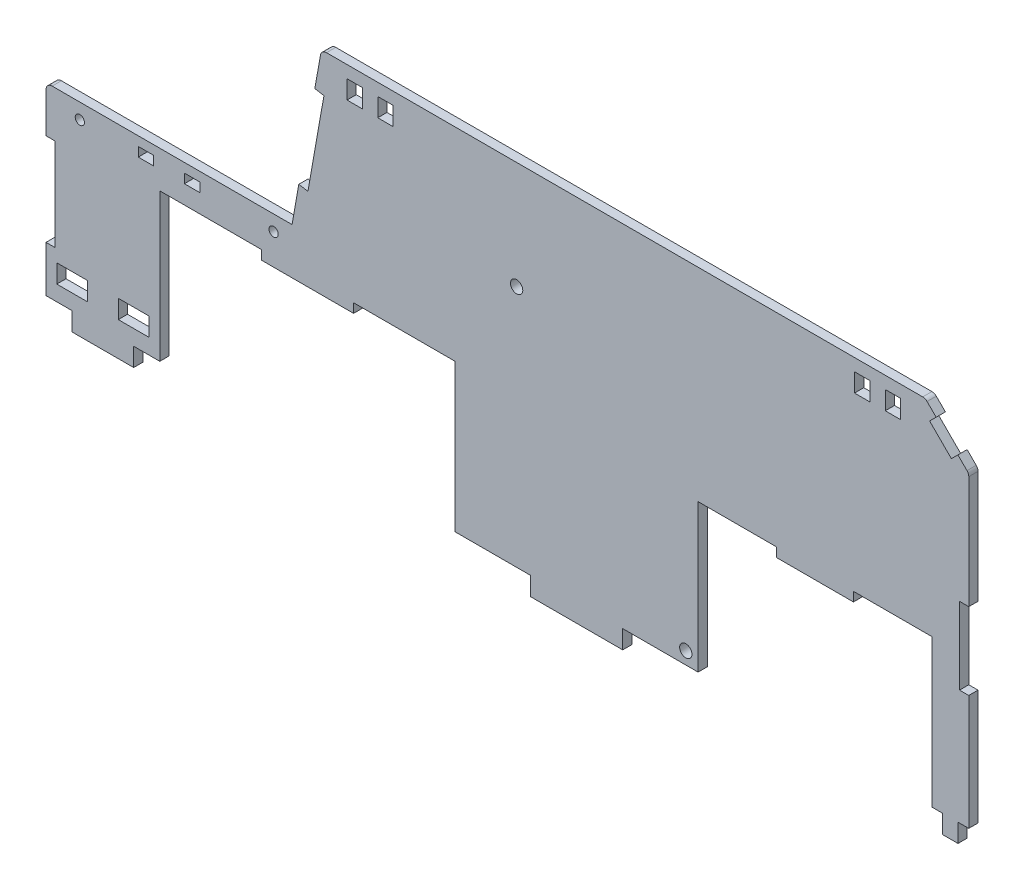
SolidWorks part; units mm, degrees
ref_plane "Front Plane" through (0, 0, 0) normal (0, 0, 1) x (1, 0, 0)
ref_plane "Top Plane" through (0, 0, 0) normal (0, 1, 0) x (1, 0, 0)
ref_plane "Right Plane" through (0, 0, 0) normal (1, 0, 0) x (0, 0, -1)
sketch "Sketch1" plane through (0, 0, 0) normal (0, 0, 1) x (1, 0, 0)
  line L0 (0, 0) -> (8.5, 0)
  line L1 (8.5, 0) -> (8.5, -6)
  line L2 (8.5, -6) -> (28.5, -6)
  line L3 (28.5, -6) -> (28.5, 0)
  line L4 (28.5, 0) -> (37, 0)
  line L5 (37, 0) -> (37, 48)
  line L6 (37, 48) -> (70, 48)
  line L7 (70, 48) -> (70, 45)
  line L8 (70, 45) -> (100, 45)
  line L9 (100, 45) -> (100, 48)
  line L10 (100, 48) -> (133, 48)
  line L11 (133, 48) -> (133, 0)
  line L12 (133, 0) -> (157.5, 0)
  line L13 (157.5, 0) -> (157.5, -6)
  line L14 (157.5, -6) -> (187.5, -6)
  line L15 (187.5, -6) -> (187.5, 0)
  line L16 (187.5, 0) -> (212, 0)
  line L17 (212, 0) -> (212, 48)
  line L18 (212, 48) -> (237.5, 48)
  line L19 (237.5, 48) -> (237.5, 45)
  line L20 (237.5, 45) -> (262.5, 45)
  line L21 (262.5, 45) -> (262.5, 48)
  line L22 (262.5, 48) -> (288, 48)
  line L23 (288, 48) -> (288, 0)
  line L24 (288, 0) -> (291.5, 0)
  line L25 (291.5, 0) -> (291.5, -6)
  line L26 (291.5, -6) -> (296.5, -6)
  line L27 (296.5, -6) -> (296.5, 0)
  line L28 (296.5, 0) -> (300, 0)
  line L29 (300, 0) -> (300, 37.4289)
  line L30 (300, 37.4289) -> (297, 37.4289)
  line L31 (297, 37.4289) -> (297, 62.4289)
  line L32 (297, 62.4289) -> (300, 62.4289)
  line L33 (300, 62.4289) -> (300, 99.8579)
  line L34 (300, 99.8579) -> (296.4645, 103.3934)
  line L35 (296.4645, 103.3934) -> (294.3431, 101.2721)
  line L36 (294.3431, 101.2721) -> (287.2721, 108.3431)
  line L37 (287.2721, 108.3431) -> (289.3934, 110.4645)
  line L38 (289.3934, 110.4645) -> (285.8579, 114)
  line L39 (285.8579, 114) -> (89.5217, 114)
  line L40 (89.5217, 114) -> (80, 60)
  line L41 (80, 60) -> (0, 60)
  line L42 (0, 60) -> (0, 0)
  dimension "D1" = 76
  dimension "D2" = 96
  dimension "D3" = 79
  dimension "D4" = 6
  dimension "D5" = 3
  dimension "D6" = 120
  dimension "D7" = 25
  dimension "D8" = 3
  dimension "D9" = 3
  dimension "D10" = 10
  dimension "D11" = 5
  dimension "D12" = 48
  dimension "D13" = 25
  dimension "D14" = 30
  dimension "D15" = 30
  dimension "D16" = 5
  dimension "D17" = 20
  dimension "D18" = 300
  dimension "D19" = 12
  dimension "D20" = 60
  dimension "D21" = 80
  dimension "D22" = 135
  dimension "D23" = 100
extrude "Boss-Extrude1" add sketch "Sketch1" along normal blind 3
sketch "Sketch2" plane through (0, 0, 0) normal (0, 0, -1) x (-1, 0, 0)
  line L0 (-212, 0) -> (-212, 48) construction
  line L1 (-187.5, 0) -> (-212, 0) construction
  circle A0 centre (-208, 4) radius 2
  circle A1 centre (-153, 79) radius 2
  dimension "D1" = 4
  dimension "D2" = 4
  dimension "D3" = 4
  dimension "D4" = 75
  dimension "D5" = 55
extrude "Cut-Extrude1" cut sketch "Sketch2" against normal through all
sketch "Sketch3" plane through (0, 0, 0) normal (0, 0, -1) x (-1, 0, 0)
  line L0 (-89.5217, 114) -> (-80, 60) construction
  line L1 (-87.4057, 102) -> (-90.3602, 101.4791)
  line L2 (-87.4057, 102) -> (-82.1963, 72.4558)
  line L3 (-82.1963, 72.4558) -> (-85.1507, 71.9348)
  line L4 (-90.3602, 101.4791) -> (-85.1507, 71.9348)
  line L5 (0, 60) -> (0, 0) construction
  line L6 (0, 45) -> (-3, 45)
  line L7 (0, 45) -> (0, 15)
  line L8 (0, 15) -> (-3, 15)
  line L9 (-3, 45) -> (-3, 15)
  line L11 (0, 0) -> (-8.5, 0) construction
  line L12 (-285.8579, 114) -> (-89.5217, 114) construction
  dimension "D1" = 12
  dimension "D2" = 30
  dimension "D3" = 3
  dimension "D4" = 15
  dimension "D5" = 30
  dimension "D6" = 3
extrude "Cut-Extrude2" cut sketch "Sketch3" against normal through all and the other way through all
sketch "Sketch4" plane through (0, 0, 0) normal (0, 0, -1) x (-1, 0, 0)
  line L0 (-37, 0) -> (-37, 48) construction
  line L1 (-33.5, 11) -> (-23.5, 11)
  line L2 (-33.5, 11) -> (-33.5, 5)
  line L3 (-33.5, 5) -> (-23.5, 5)
  line L4 (-23.5, 11) -> (-23.5, 5)
  line L5 (-13.5, 11) -> (-3.5, 11)
  line L6 (-13.5, 11) -> (-13.5, 5)
  line L7 (-13.5, 5) -> (-3.5, 5)
  line L8 (-3.5, 11) -> (-3.5, 5)
  line L9 (-28.5, 0) -> (-37, 0) construction
  dimension "D1" = 10
  dimension "D2" = 6
  dimension "D3" = 3.5
  dimension "D4" = 30
  dimension "D5" = 5
extrude "Cut-Extrude3" cut sketch "Sketch4" against normal through all
sketch "Sketch5" plane through (0, 0, 0) normal (0, 0, -1) x (-1, 0, 0)
  line L0 (-80, 60) -> (0, 60) construction
  line L1 (0, 60) -> (0, 45) construction
  line L3 (-50, 57) -> (-45, 57)
  line L4 (-50, 57) -> (-50, 54)
  line L5 (-50, 54) -> (-45, 54)
  line L6 (-45, 57) -> (-45, 54)
  line L7 (-35, 57) -> (-30, 57)
  line L8 (-35, 57) -> (-35, 54)
  line L9 (-35, 54) -> (-30, 54)
  line L10 (-30, 57) -> (-30, 54)
  circle A0 centre (-11, 55) radius 1.5
  circle A1 centre (-74, 55) radius 1.5
  dimension "D1" = 5
  dimension "D2" = 3
  dimension "D3" = 11
  dimension "D9" = 3
  dimension "D10" = 5
  dimension "D11" = 74
  dimension "D4" = 3
  dimension "D5" = 5
  dimension "D6" = 10
  dimension "D7" = 3
  dimension "D8" = 30
extrude "Cut-Extrude4" cut sketch "Sketch5" against normal through all
sketch "Sketch6" plane through (0, 0, 0) normal (0, 0, -1) x (-1, 0, 0)
  line L0 (-285.8579, 114) -> (-89.5217, 114) construction
  line L1 (-277.8579, 110) -> (-272.8579, 110)
  line L2 (-277.8579, 110) -> (-277.8579, 104)
  line L3 (-277.8579, 104) -> (-272.8579, 104)
  line L4 (-272.8579, 110) -> (-272.8579, 104)
  line L5 (-267.8579, 110) -> (-262.8579, 110)
  line L6 (-267.8579, 110) -> (-267.8579, 104)
  line L7 (-267.8579, 104) -> (-262.8579, 104)
  line L8 (-262.8579, 110) -> (-262.8579, 104)
  line L9 (-112.8579, 110) -> (-107.8579, 110)
  line L10 (-112.8579, 110) -> (-112.8579, 104)
  line L11 (-112.8579, 104) -> (-107.8579, 104)
  line L12 (-107.8579, 110) -> (-107.8579, 104)
  line L13 (-102.8579, 110) -> (-97.8579, 110)
  line L14 (-102.8579, 110) -> (-102.8579, 104)
  line L15 (-102.8579, 104) -> (-97.8579, 104)
  line L16 (-97.8579, 110) -> (-97.8579, 104)
  dimension "D1" = 4
  dimension "D2" = 5
  dimension "D3" = 5
  dimension "D4" = 6
  dimension "D5" = 5
  dimension "D6" = 150
  dimension "D7" = 8
extrude "Cut-Extrude5" cut sketch "Sketch6" against normal through all
fillet "Fillet1" radius 2 4 edges at (0, 60, 1.5) (89.5217, 114, 1.5) (285.8579, 114, 1.5) (300, 99.8579, 1.5)
